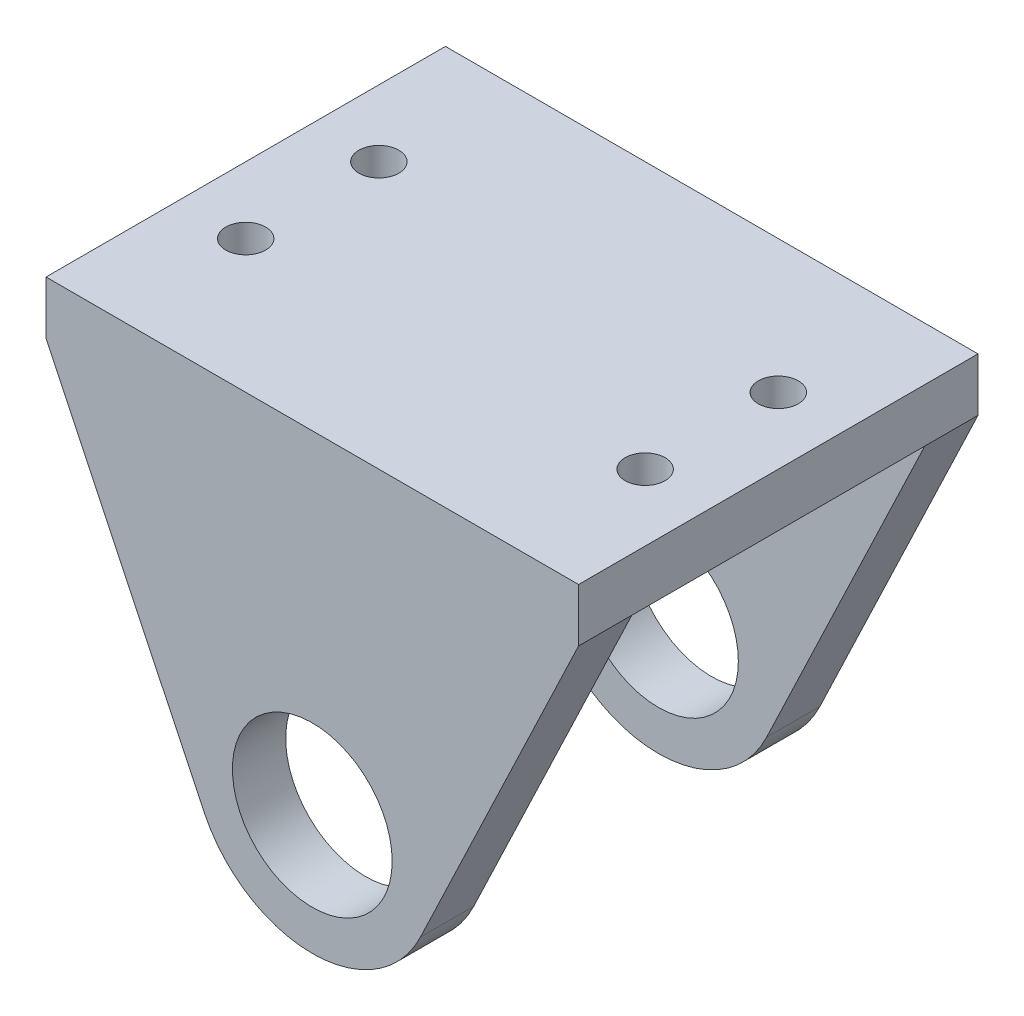
SolidWorks part; units mm, degrees
material "6061 合金"
ref_plane "前视基准面" through (0, 0, 0) normal (0, 0, 1) x (1, 0, 0)
ref_plane "上视基准面" through (0, 0, 0) normal (0, 1, 0) x (1, 0, 0)
ref_plane "右视基准面" through (0, 0, 0) normal (1, 0, 0) x (0, 0, -1)
sketch "草图1" plane through (0, 0, 0) normal (0, 1, 0) x (1, 0, 0)
  line L1 (-20, -10) -> (20, -10)
  line L2 (-20, -10) -> (-20, 10)
  line L3 (-20, 10) -> (20, 10)
  line L4 (20, -10) -> (20, 10)
  line L5 (-20, -10) -> (20, 10) construction
  line L6 (-20, 10) -> (20, -10) construction
  point P0 (0, 0)
  dimension "D1" = 40
  dimension "D2" = 20
extrude "凸台-拉伸1" add sketch "草图1" against normal blind 4
sketch "草图2" plane through (0, 0, 10) normal (0, 0, 1) x (1, 0, 0)
  line L0 (20, -4) -> (20, 0)
  line L1 (20, 0) -> (-20, 0)
  line L2 (-20, 0) -> (20, 0) construction
  line L3 (-20, 0) -> (-20, -4)
  line L4 (-20, -4) -> (-8.1217, -28.8778)
  line L5 (-20, -4) -> (-20, 0) construction
  line L6 (20, -4) -> (8.1217, -28.8778)
  arc A0 (-8.1217, -28.8778) -> (8.1217, -28.8778) centre (0, -25) ccw
  circle A1 centre (0, -25) radius 6
  dimension "D2" = 9
  dimension "D4" = 12
  dimension "D1" = 25
  dimension "D3" = 4
extrude "凸台-拉伸2" add sketch "草图2" along normal blind 5
sketch "草图3" plane through (0, 0, 10) normal (0, 0, -1) x (-1, 0, 0)
  line L0 (20, -4) -> (-20, -4) construction
  line L1 (-20, -39) -> (20, -39)
  line L2 (-20, -39) -> (-20, -4)
  line L3 (-20, -4) -> (20, -4)
  line L4 (20, -39) -> (20, -4)
  point P0 (0, -25)
  dimension "D1" = 35
  dimension "D2" = 40
extrude "切除-拉伸1" cut sketch "草图3" against normal blind 1
fillet "圆角2" [suppressed] radius 3
mirror "镜向1" about plane through (0, 0, 0) normal (0, 0, 1) of "凸台-拉伸2", "切除-拉伸1", "圆角2"
sketch "草图4" [suppressed] plane through (0, 0, 0) normal (0, 1, 0) x (1, 0, 0)
  line L0 (-20, 0) -> (20, 0) construction
  line L1 (-20, 15) -> (-20, -15) construction
  line L2 (20, -15) -> (20, 15) construction
  line L3 (0, 15) -> (0, -15) construction
  line L4 (20, 15) -> (-20, 15) construction
  line L5 (20, -15) -> (-20, -15) construction
  circle A0 centre (-10, 0) radius 2.05
  circle A1 centre (10, 0) radius 2.05
  dimension "D1" = 4.1
  dimension "D2" = 20
extrude "切除-拉伸2" [suppressed] cut sketch "草图4" against normal through all
sketch "草图5" plane through (0, 0, 15) normal (0, 0, 1) x (1, 0, 0)
  line L0 (-36.1153, -14) -> (49963.8847, -14) construction
  line L1 (0, 0) -> (0, 50000) construction
  line L2 (20, 0) -> (-20, 0) construction
  circle A0 centre (-7.5, -14) radius 2.1
  circle A1 centre (7.5, -14) radius 2.1
  point P11 (0, 0)
  dimension "D2" = 4.2
  dimension "D3" = 15
  dimension "D1" = 14
fillet "圆角3" [suppressed] radius 1
sketch "草图6" plane through (0, -4, 0) normal (0, -1, 0) x (1, 0, 0)
  line L0 (0, 0) -> (0, -29.6186) construction
  line L2 (20, 15) -> (-20, 15) construction
  line L3 (23.0767, 0) -> (-23.237, 0) construction
  circle A0 centre (-15, 5) radius 1.5
  circle A1 centre (15, 5) radius 1.5
  circle A2 centre (-15, -5) radius 1.5
  circle A3 centre (15, -5) radius 1.5
  dimension "D1" = 30
  dimension "D2" = 3
  dimension "D3" = 10
extrude "切除-拉伸3" cut sketch "草图6" against normal blind 10
